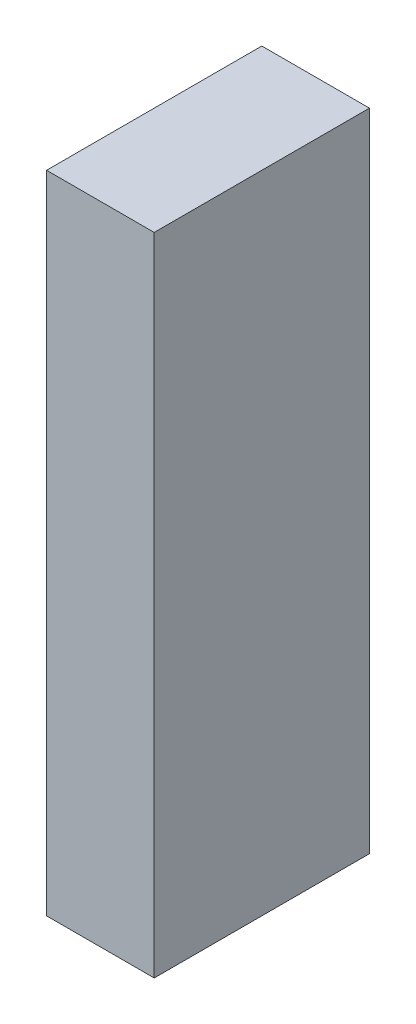
SolidWorks part; units mm, degrees
ref_plane "Front Plane" through (0, 0, 0) normal (0, 0, 1) x (1, 0, 0)
ref_plane "Top Plane" through (0, 0, 0) normal (0, 1, 0) x (1, 0, 0)
ref_plane "Right Plane" through (0, 0, 0) normal (1, 0, 0) x (0, 0, -1)
sketch "Sketch1" plane through (0, 0, 0) normal (1, 0, 0) x (0, 0, -1)
  line L1 (-19.05, 57.15) -> (19.05, 57.15)
  line L2 (-19.05, 57.15) -> (-19.05, -57.15)
  line L3 (-19.05, -57.15) -> (19.05, -57.15)
  line L4 (19.05, 57.15) -> (19.05, -57.15)
  line L5 (-19.05, 57.15) -> (19.05, -57.15) construction
  line L6 (-19.05, -57.15) -> (19.05, 57.15) construction
  point P0 (0, 0)
  dimension "D1" = 38.1
  dimension "D2" = 114.3
extrude "Boss-Extrude1" add sketch "Sketch1" along normal blind 19.05
